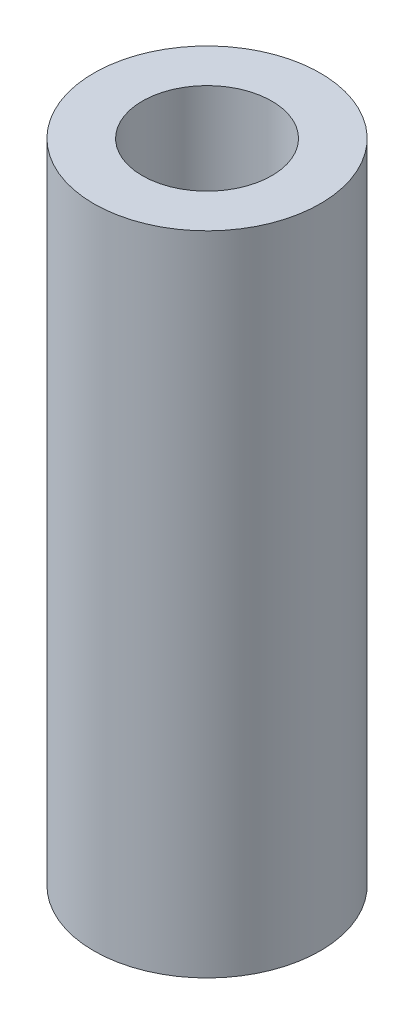
SolidWorks part; units mm, degrees
material "尼龙 101"
ref_plane "前视基准面" through (0, 0, 0) normal (0, 0, 1) x (1, 0, 0)
ref_plane "上视基准面" through (0, 0, 0) normal (0, 1, 0) x (1, 0, 0)
ref_plane "右视基准面" through (0, 0, 0) normal (1, 0, 0) x (0, 0, -1)
sketch "草图1" plane through (0, 0, 0) normal (0, 1, 0) x (1, 0, 0)
  circle A0 centre (0, 0) radius 3.5
  circle A1 centre (0, 0) radius 2
  dimension "D1" = 4
  dimension "D2" = 7
extrude "凸台-拉伸1" add sketch "草图1" along normal blind 20
